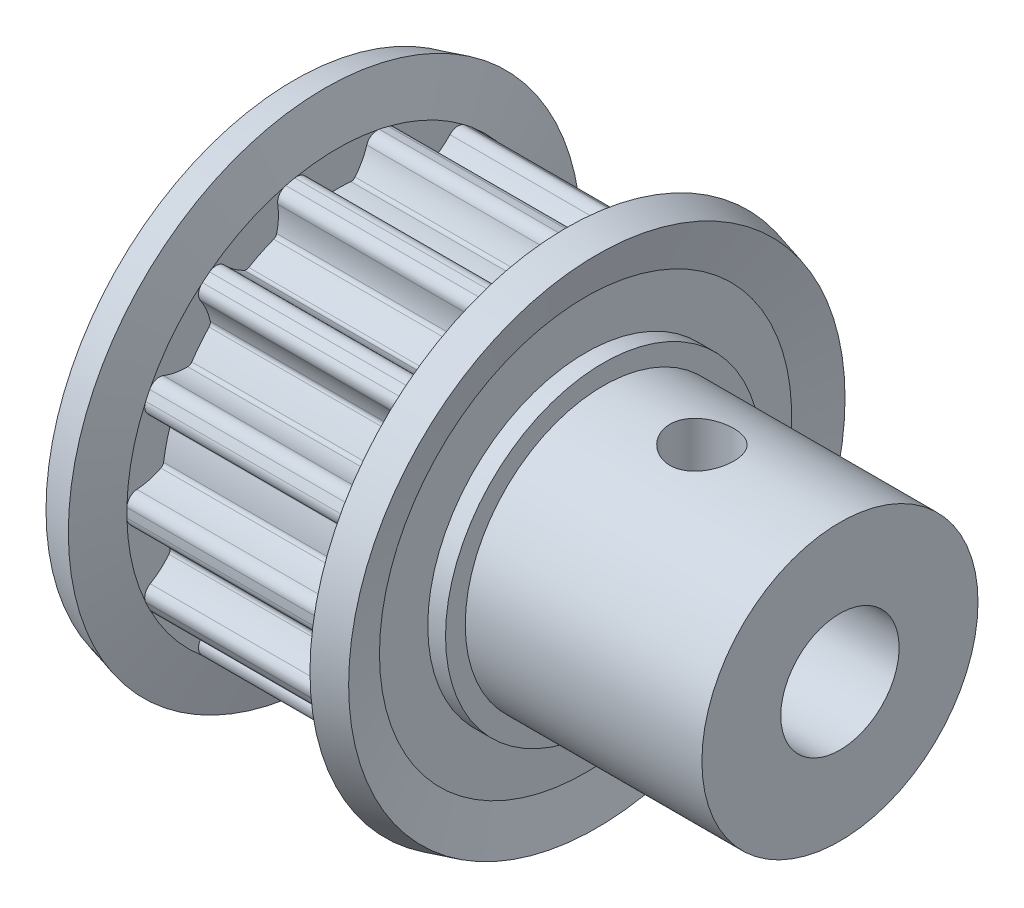
SolidWorks part; units mm, degrees
ref_plane "Front Plane" through (0, 0, 0) normal (0, 0, 1) x (1, 0, 0)
ref_plane "Top Plane" through (0, 0, 0) normal (0, 1, 0) x (1, 0, 0)
ref_plane "Right Plane" through (0, 0, 0) normal (1, 0, 0) x (0, 0, -1)
ref_plane "Plane1" through (0, 0, 0) normal (0, 0, 1) x (1, 0, 0)
sketch "Sketch1" plane through (0, 0, 0) normal (0, 0, 1) x (1, 0, 0)
  line L0 (0, 0) -> (0, 8)
  line L1 (0, 8) -> (0.9, 8)
  line L2 (0.9, 8) -> (0.9, 10.4494)
  line L3 (0.9, 10.4494) -> (0.3275, 12.5859)
  line L4 (0.3275, 12.5859) -> (1.873, 13)
  line L5 (1.873, 13) -> (2.5, 10.66)
  line L6 (2.5, 10.66) -> (13.5, 10.66)
  line L7 (13.5, 10.66) -> (14.127, 13)
  line L8 (14.127, 13) -> (15.6725, 12.5859)
  line L9 (15.6725, 12.5859) -> (15.1, 10.4494)
  line L10 (15.1, 10.4494) -> (15.1, 8)
  line L11 (15.1, 8) -> (16, 8)
  line L12 (16, 8) -> (16, 7)
  line L13 (16, 7) -> (28, 7)
  line L14 (28, 7) -> (28, 0)
  line L15 (28, 0) -> (0, 0)
  line L16 (28, 0) -> (0, 0) construction
revolve "Revolve1" add sketch "Sketch1" angle 360 about L16
ref_plane "Plane2" through (0, 0, 0) normal (0, 0, 1) x (1, 0, 0)
sketch "Sketch2" plane through (0, 0, 0) normal (0, 0, 1) x (1, 0, 0)
  line L0 (0, 0) -> (0, 3)
  line L1 (0, 3) -> (28, 3)
  line L2 (28, 3) -> (28, 0)
  line L3 (28, 0) -> (0, 0)
  line L4 (28, 0) -> (0, 0) construction
revolve "Cut-Revolve1" cut sketch "Sketch2" angle 360 about L4
ref_plane "Plane3" through (2.5, 0, 0) normal (1, 0, 0) x (0, 0, -1)
sketch "Sketch3" plane through (2.5, 0, 0) normal (1, 0, 0) x (0, 0, -1)
  line L0 (2.1438, 10.4422) -> (2.1438, 14.2133)
  line L1 (2.1438, 14.2133) -> (-2.1438, 14.2133)
  line L2 (-2.1438, 14.2133) -> (-2.1438, 10.4422)
  arc A0 (-2.1438, 10.4422) -> (-1.5071, 10.0641) centre (-2.0332, 9.9035) cw
  arc A1 (-1.5071, 10.0641) -> (-0.9152, 8.9537) centre (1.625, 11.0208) ccw
  arc A2 (-0.9152, 8.9537) -> (-0.7015, 8.8623) centre (-0.7213, 9.1115) ccw
  arc A3 (-0.7015, 8.8623) -> (0.7015, 8.8623) centre (0, 0) cw
  arc A4 (0.7015, 8.8623) -> (0.9152, 8.9537) centre (0.7213, 9.1115) ccw
  arc A5 (0.9152, 8.9537) -> (1.5071, 10.0641) centre (-1.625, 11.0208) ccw
  arc A6 (1.5071, 10.0641) -> (2.1438, 10.4422) centre (2.0332, 9.9035) cw
extrude "Cut-Extrude1" cut sketch "Sketch3" along normal blind 11
ref_plane "Plane4" through (2.5, 0, 0) normal (1, 0, 0) x (0, 0, -1)
sketch "Sketch4" plane through (2.5, 0, 0) normal (1, 0, 0) x (0, 0, -1)
  line L0 (6.4622, 8.478) -> (8.0984, 11.8756)
  line L1 (8.0984, 11.8756) -> (4.2355, 13.7359)
  line L2 (4.2355, 13.7359) -> (2.5992, 10.3383)
  arc A0 (2.5992, 10.3383) -> (3.0088, 9.7214) centre (2.4651, 9.8049) cw
  arc A1 (3.0088, 9.7214) -> (3.0603, 8.4641) centre (6.2458, 9.2244) ccw
  arc A2 (3.0603, 8.4641) -> (3.2131, 8.289) centre (3.3035, 8.5221) ccw
  arc A3 (3.2131, 8.289) -> (4.4773, 7.6802) centre (0, 0) cw
  arc A4 (4.4773, 7.6802) -> (4.7094, 7.6699) centre (4.6032, 7.8962) ccw
  arc A5 (4.7094, 7.6699) -> (5.7245, 8.4135) centre (3.3177, 10.6345) ccw
  arc A6 (5.7245, 8.4135) -> (6.4622, 8.478) centre (6.1288, 8.0406) cw
extrude "Cut-Extrude2" cut sketch "Sketch4" along normal blind 11
ref_plane "Plane5" through (2.5, 0, 0) normal (1, 0, 0) x (0, 0, -1)
sketch "Sketch5" plane through (2.5, 0, 0) normal (1, 0, 0) x (0, 0, -1)
  line L0 (9.5007, 4.8346) -> (12.449, 7.1858)
  line L1 (12.449, 7.1858) -> (9.7758, 10.5379)
  line L2 (9.7758, 10.5379) -> (6.8274, 8.1867)
  arc A0 (6.8274, 8.1867) -> (6.9288, 7.4532) centre (6.4752, 7.7643) cw
  arc A1 (6.9288, 7.4532) -> (6.4297, 6.2981) centre (9.6296, 5.6009) ccw
  arc A2 (6.4297, 6.2981) -> (6.4914, 6.074) centre (6.6739, 6.2448) ccw
  arc A3 (6.4914, 6.074) -> (7.3662, 4.977) centre (0, 0) cw
  arc A4 (7.3662, 4.977) -> (7.5709, 4.867) centre (7.5734, 5.117) ccw
  arc A5 (7.5709, 4.867) -> (8.8081, 5.0965) centre (7.6033, 8.1419) ccw
  arc A6 (8.8081, 5.0965) -> (9.5007, 4.8346) centre (9.0105, 4.5851) cw
extrude "Cut-Extrude3" cut sketch "Sketch5" along normal blind 11
ref_plane "Plane6" through (2.5, 0, 0) normal (1, 0, 0) x (0, 0, -1)
sketch "Sketch6" plane through (2.5, 0, 0) normal (1, 0, 0) x (0, 0, -1)
  line L0 (10.6574, 0.2336) -> (14.334, 1.0728)
  line L1 (14.334, 1.0728) -> (13.3799, 5.2528)
  line L2 (13.3799, 5.2528) -> (9.7034, 4.4136)
  arc A0 (9.7034, 4.4136) -> (9.4764, 3.7088) centre (9.2027, 4.1859) cw
  arc A1 (9.4764, 3.7088) -> (8.5256, 2.8846) centre (11.1061, 0.8681) ccw
  arc A2 (8.5256, 2.8846) -> (8.484, 2.656) centre (8.7226, 2.7307) ccw
  arc A3 (8.484, 2.656) -> (8.7962, 1.2881) centre (0, 0) cw
  arc A4 (8.7962, 1.2881) -> (8.9329, 1.1001) centre (9.0436, 1.3243) ccw
  arc A5 (8.9329, 1.1001) -> (10.1472, 0.7701) centre (10.3829, 4.0366) ccw
  arc A6 (10.1472, 0.7701) -> (10.6574, 0.2336) centre (10.1076, 0.2216) cw
extrude "Cut-Extrude4" cut sketch "Sketch6" along normal blind 11
ref_plane "Plane7" through (2.5, 0, 0) normal (1, 0, 0) x (0, 0, -1)
sketch "Sketch7" plane through (2.5, 0, 0) normal (1, 0, 0) x (0, 0, -1)
  line L0 (9.7034, -4.4136) -> (13.3799, -5.2528)
  line L1 (13.3799, -5.2528) -> (14.334, -1.0728)
  line L2 (14.334, -1.0728) -> (10.6574, -0.2336)
  arc A0 (10.6574, -0.2336) -> (10.1472, -0.7701) centre (10.1076, -0.2216) cw
  arc A1 (10.1472, -0.7701) -> (8.9329, -1.1001) centre (10.3829, -4.0366) ccw
  arc A2 (8.9329, -1.1001) -> (8.7962, -1.2881) centre (9.0436, -1.3243) ccw
  arc A3 (8.7962, -1.2881) -> (8.484, -2.656) centre (0, 0) cw
  arc A4 (8.484, -2.656) -> (8.5256, -2.8846) centre (8.7226, -2.7307) ccw
  arc A5 (8.5256, -2.8846) -> (9.4764, -3.7088) centre (11.1061, -0.8681) ccw
  arc A6 (9.4764, -3.7088) -> (9.7034, -4.4136) centre (9.2027, -4.1859) cw
extrude "Cut-Extrude5" cut sketch "Sketch7" along normal blind 11
ref_plane "Plane8" through (2.5, 0, 0) normal (1, 0, 0) x (0, 0, -1)
sketch "Sketch8" plane through (2.5, 0, 0) normal (1, 0, 0) x (0, 0, -1)
  line L0 (6.8274, -8.1867) -> (9.7758, -10.5379)
  line L1 (9.7758, -10.5379) -> (12.449, -7.1858)
  line L2 (12.449, -7.1858) -> (9.5007, -4.8346)
  arc A0 (9.5007, -4.8346) -> (8.8081, -5.0965) centre (9.0105, -4.5851) cw
  arc A1 (8.8081, -5.0965) -> (7.5709, -4.867) centre (7.6033, -8.1419) ccw
  arc A2 (7.5709, -4.867) -> (7.3662, -4.977) centre (7.5734, -5.117) ccw
  arc A3 (7.3662, -4.977) -> (6.4914, -6.074) centre (0, 0) cw
  arc A4 (6.4914, -6.074) -> (6.4297, -6.2981) centre (6.6739, -6.2448) ccw
  arc A5 (6.4297, -6.2981) -> (6.9288, -7.4532) centre (9.6296, -5.6009) ccw
  arc A6 (6.9288, -7.4532) -> (6.8274, -8.1867) centre (6.4752, -7.7643) cw
extrude "Cut-Extrude6" cut sketch "Sketch8" along normal blind 11
ref_plane "Plane9" through (2.5, 0, 0) normal (1, 0, 0) x (0, 0, -1)
sketch "Sketch9" plane through (2.5, 0, 0) normal (1, 0, 0) x (0, 0, -1)
  line L0 (2.5992, -10.3383) -> (4.2355, -13.7359)
  line L1 (4.2355, -13.7359) -> (8.0984, -11.8756)
  line L2 (8.0984, -11.8756) -> (6.4622, -8.478)
  arc A0 (6.4622, -8.478) -> (5.7245, -8.4135) centre (6.1288, -8.0406) cw
  arc A1 (5.7245, -8.4135) -> (4.7094, -7.6699) centre (3.3177, -10.6345) ccw
  arc A2 (4.7094, -7.6699) -> (4.4773, -7.6802) centre (4.6032, -7.8962) ccw
  arc A3 (4.4773, -7.6802) -> (3.2131, -8.289) centre (0, 0) cw
  arc A4 (3.2131, -8.289) -> (3.0603, -8.4641) centre (3.3035, -8.5221) ccw
  arc A5 (3.0603, -8.4641) -> (3.0088, -9.7214) centre (6.2458, -9.2244) ccw
  arc A6 (3.0088, -9.7214) -> (2.5992, -10.3383) centre (2.4651, -9.8049) cw
extrude "Cut-Extrude7" cut sketch "Sketch9" along normal blind 11
ref_plane "Plane10" through (2.5, 0, 0) normal (1, 0, 0) x (0, 0, -1)
sketch "Sketch10" plane through (2.5, 0, 0) normal (1, 0, 0) x (0, 0, -1)
  line L0 (-2.1438, -10.4422) -> (-2.1438, -14.2133)
  line L1 (-2.1438, -14.2133) -> (2.1438, -14.2133)
  line L2 (2.1438, -14.2133) -> (2.1438, -10.4422)
  arc A0 (2.1438, -10.4422) -> (1.5071, -10.0641) centre (2.0332, -9.9035) cw
  arc A1 (1.5071, -10.0641) -> (0.9152, -8.9537) centre (-1.625, -11.0208) ccw
  arc A2 (0.9152, -8.9537) -> (0.7015, -8.8623) centre (0.7213, -9.1115) ccw
  arc A3 (0.7015, -8.8623) -> (-0.7015, -8.8623) centre (0, 0) cw
  arc A4 (-0.7015, -8.8623) -> (-0.9152, -8.9537) centre (-0.7213, -9.1115) ccw
  arc A5 (-0.9152, -8.9537) -> (-1.5071, -10.0641) centre (1.625, -11.0208) ccw
  arc A6 (-1.5071, -10.0641) -> (-2.1438, -10.4422) centre (-2.0332, -9.9035) cw
extrude "Cut-Extrude8" cut sketch "Sketch10" along normal blind 11
ref_plane "Plane11" through (2.5, 0, 0) normal (1, 0, 0) x (0, 0, -1)
sketch "Sketch11" plane through (2.5, 0, 0) normal (1, 0, 0) x (0, 0, -1)
  line L0 (-6.4622, -8.478) -> (-8.0984, -11.8756)
  line L1 (-8.0984, -11.8756) -> (-4.2355, -13.7359)
  line L2 (-4.2355, -13.7359) -> (-2.5992, -10.3383)
  arc A0 (-2.5992, -10.3383) -> (-3.0088, -9.7214) centre (-2.4651, -9.8049) cw
  arc A1 (-3.0088, -9.7214) -> (-3.0603, -8.4641) centre (-6.2458, -9.2244) ccw
  arc A2 (-3.0603, -8.4641) -> (-3.2131, -8.289) centre (-3.3035, -8.5221) ccw
  arc A3 (-3.2131, -8.289) -> (-4.4773, -7.6802) centre (0, 0) cw
  arc A4 (-4.4773, -7.6802) -> (-4.7094, -7.6699) centre (-4.6032, -7.8962) ccw
  arc A5 (-4.7094, -7.6699) -> (-5.7245, -8.4135) centre (-3.3177, -10.6345) ccw
  arc A6 (-5.7245, -8.4135) -> (-6.4622, -8.478) centre (-6.1288, -8.0406) cw
extrude "Cut-Extrude9" cut sketch "Sketch11" along normal blind 11
ref_plane "Plane12" through (2.5, 0, 0) normal (1, 0, 0) x (0, 0, -1)
sketch "Sketch12" plane through (2.5, 0, 0) normal (1, 0, 0) x (0, 0, -1)
  line L0 (-9.5007, -4.8346) -> (-12.449, -7.1858)
  line L1 (-12.449, -7.1858) -> (-9.7758, -10.5379)
  line L2 (-9.7758, -10.5379) -> (-6.8274, -8.1867)
  arc A0 (-6.8274, -8.1867) -> (-6.9288, -7.4532) centre (-6.4752, -7.7643) cw
  arc A1 (-6.9288, -7.4532) -> (-6.4297, -6.2981) centre (-9.6296, -5.6009) ccw
  arc A2 (-6.4297, -6.2981) -> (-6.4914, -6.074) centre (-6.6739, -6.2448) ccw
  arc A3 (-6.4914, -6.074) -> (-7.3662, -4.977) centre (0, 0) cw
  arc A4 (-7.3662, -4.977) -> (-7.5709, -4.867) centre (-7.5734, -5.117) ccw
  arc A5 (-7.5709, -4.867) -> (-8.8081, -5.0965) centre (-7.6033, -8.1419) ccw
  arc A6 (-8.8081, -5.0965) -> (-9.5007, -4.8346) centre (-9.0105, -4.5851) cw
extrude "Cut-Extrude10" cut sketch "Sketch12" along normal blind 11
ref_plane "Plane13" through (2.5, 0, 0) normal (1, 0, 0) x (0, 0, -1)
sketch "Sketch13" plane through (2.5, 0, 0) normal (1, 0, 0) x (0, 0, -1)
  line L0 (-10.6574, -0.2336) -> (-14.334, -1.0728)
  line L1 (-14.334, -1.0728) -> (-13.3799, -5.2528)
  line L2 (-13.3799, -5.2528) -> (-9.7034, -4.4136)
  arc A0 (-9.7034, -4.4136) -> (-9.4764, -3.7088) centre (-9.2027, -4.1859) cw
  arc A1 (-9.4764, -3.7088) -> (-8.5256, -2.8846) centre (-11.1061, -0.8681) ccw
  arc A2 (-8.5256, -2.8846) -> (-8.484, -2.656) centre (-8.7226, -2.7307) ccw
  arc A3 (-8.484, -2.656) -> (-8.7962, -1.2881) centre (0, 0) cw
  arc A4 (-8.7962, -1.2881) -> (-8.9329, -1.1001) centre (-9.0436, -1.3243) ccw
  arc A5 (-8.9329, -1.1001) -> (-10.1472, -0.7701) centre (-10.3829, -4.0366) ccw
  arc A6 (-10.1472, -0.7701) -> (-10.6574, -0.2336) centre (-10.1076, -0.2216) cw
extrude "Cut-Extrude11" cut sketch "Sketch13" along normal blind 11
ref_plane "Plane14" through (2.5, 0, 0) normal (1, 0, 0) x (0, 0, -1)
sketch "Sketch14" plane through (2.5, 0, 0) normal (1, 0, 0) x (0, 0, -1)
  line L0 (-9.7034, 4.4136) -> (-13.3799, 5.2528)
  line L1 (-13.3799, 5.2528) -> (-14.334, 1.0728)
  line L2 (-14.334, 1.0728) -> (-10.6574, 0.2336)
  arc A0 (-10.6574, 0.2336) -> (-10.1472, 0.7701) centre (-10.1076, 0.2216) cw
  arc A1 (-10.1472, 0.7701) -> (-8.9329, 1.1001) centre (-10.3829, 4.0366) ccw
  arc A2 (-8.9329, 1.1001) -> (-8.7962, 1.2881) centre (-9.0436, 1.3243) ccw
  arc A3 (-8.7962, 1.2881) -> (-8.484, 2.656) centre (0, 0) cw
  arc A4 (-8.484, 2.656) -> (-8.5256, 2.8846) centre (-8.7226, 2.7307) ccw
  arc A5 (-8.5256, 2.8846) -> (-9.4764, 3.7088) centre (-11.1061, 0.8681) ccw
  arc A6 (-9.4764, 3.7088) -> (-9.7034, 4.4136) centre (-9.2027, 4.1859) cw
extrude "Cut-Extrude12" cut sketch "Sketch14" along normal blind 11
ref_plane "Plane15" through (2.5, 0, 0) normal (1, 0, 0) x (0, 0, -1)
sketch "Sketch15" plane through (2.5, 0, 0) normal (1, 0, 0) x (0, 0, -1)
  line L0 (-6.8274, 8.1867) -> (-9.7758, 10.5379)
  line L1 (-9.7758, 10.5379) -> (-12.449, 7.1858)
  line L2 (-12.449, 7.1858) -> (-9.5007, 4.8346)
  arc A0 (-9.5007, 4.8346) -> (-8.8081, 5.0965) centre (-9.0105, 4.5851) cw
  arc A1 (-8.8081, 5.0965) -> (-7.5709, 4.867) centre (-7.6033, 8.1419) ccw
  arc A2 (-7.5709, 4.867) -> (-7.3662, 4.977) centre (-7.5734, 5.117) ccw
  arc A3 (-7.3662, 4.977) -> (-6.4914, 6.074) centre (0, 0) cw
  arc A4 (-6.4914, 6.074) -> (-6.4297, 6.2981) centre (-6.6739, 6.2448) ccw
  arc A5 (-6.4297, 6.2981) -> (-6.9288, 7.4532) centre (-9.6296, 5.6009) ccw
  arc A6 (-6.9288, 7.4532) -> (-6.8274, 8.1867) centre (-6.4752, 7.7643) cw
extrude "Cut-Extrude13" cut sketch "Sketch15" along normal blind 11
ref_plane "Plane16" through (2.5, 0, 0) normal (1, 0, 0) x (0, 0, -1)
sketch "Sketch16" plane through (2.5, 0, 0) normal (1, 0, 0) x (0, 0, -1)
  line L0 (-2.5992, 10.3383) -> (-4.2355, 13.7359)
  line L1 (-4.2355, 13.7359) -> (-8.0984, 11.8756)
  line L2 (-8.0984, 11.8756) -> (-6.4622, 8.478)
  arc A0 (-6.4622, 8.478) -> (-5.7245, 8.4135) centre (-6.1288, 8.0406) cw
  arc A1 (-5.7245, 8.4135) -> (-4.7094, 7.6699) centre (-3.3177, 10.6345) ccw
  arc A2 (-4.7094, 7.6699) -> (-4.4773, 7.6802) centre (-4.6032, 7.8962) ccw
  arc A3 (-4.4773, 7.6802) -> (-3.2131, 8.289) centre (0, 0) cw
  arc A4 (-3.2131, 8.289) -> (-3.0603, 8.4641) centre (-3.3035, 8.5221) ccw
  arc A5 (-3.0603, 8.4641) -> (-3.0088, 9.7214) centre (-6.2458, 9.2244) ccw
  arc A6 (-3.0088, 9.7214) -> (-2.5992, 10.3383) centre (-2.4651, 9.8049) cw
extrude "Cut-Extrude14" cut sketch "Sketch16" along normal blind 11
ref_plane "Plane17" through (21, 0, 0) normal (1, 0, 0) x (0, 0, -1)
sketch "Sketch17" plane through (21, 0, 0) normal (1, 0, 0) x (0, 0, -1)
  line L0 (0, 7) -> (1.621, 7)
  line L1 (1.621, 7) -> (1.621, 0)
  line L2 (1.621, 0) -> (0, 0)
  line L3 (0, 0) -> (0, 7)
  line L4 (0, 0) -> (0, 7) construction
revolve "Cut-Revolve2" cut sketch "Sketch17" angle 360 about L4
ref_plane "Plane18" through (21, 0, 0) normal (1, 0, 0) x (0, 0, -1)
sketch "Sketch18" plane through (21, 0, 0) normal (1, 0, 0) x (0, 0, -1)
  line L0 (6.0622, -3.5) -> (5.2517, -4.9038)
  line L1 (5.2517, -4.9038) -> (-0.8105, -1.4038)
  line L2 (-0.8105, -1.4038) -> (0, 0)
  line L3 (0, 0) -> (6.0622, -3.5)
  line L4 (0, 0) -> (6.0622, -3.5) construction
revolve "Cut-Revolve3" cut sketch "Sketch18" angle 360 about L4
